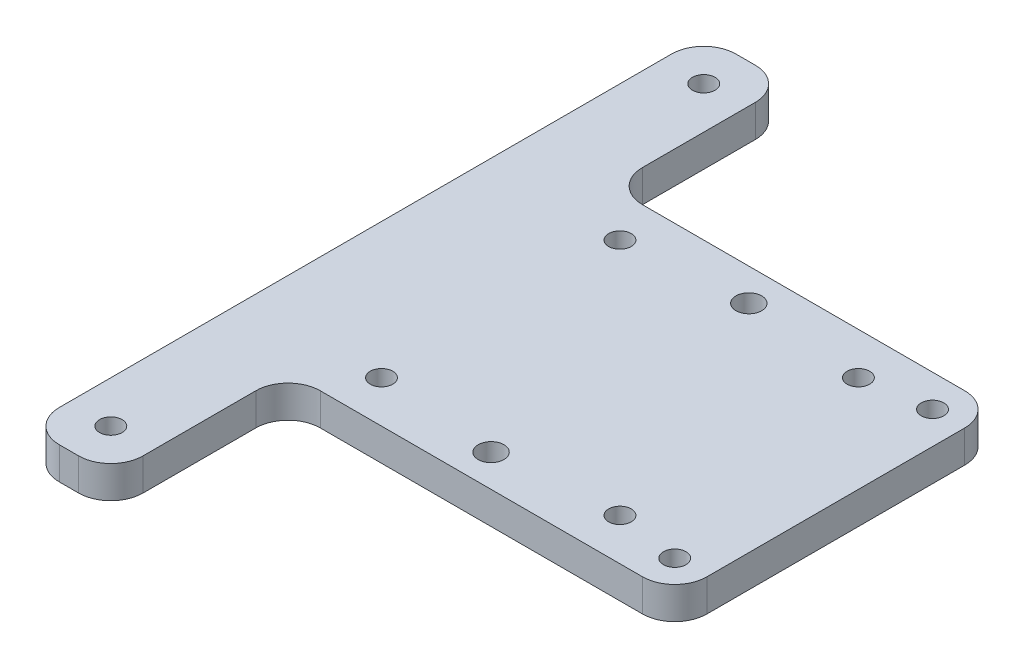
SolidWorks part; units mm, degrees
ref_plane "정면" through (0, 0, 0) normal (0, 0, 1) x (1, 0, 0)
ref_plane "윗면" through (0, 0, 0) normal (0, 1, 0) x (1, 0, 0)
ref_plane "우측면" through (0, 0, 0) normal (1, 0, 0) x (0, 0, -1)
sketch "스케치2" plane through (0, 0, 0) normal (0, 1, 0) x (1, 0, 0)
  line L0 (-60, -25) -> (-60, -52.5)
  line L1 (-60, 25) -> (0, 25)
  line L3 (-60, -25) -> (0, -25)
  line L4 (0, 25) -> (0, -25)
  line L5 (-60, 25) -> (0, -25) construction
  line L6 (-60, -25) -> (0, 25) construction
  line L11 (-73, 52.5) -> (-60, 52.5)
  line L12 (-73, 52.5) -> (-73, -52.5)
  line L13 (-73, -52.5) -> (-60, -52.5)
  line L14 (-60, 52.5) -> (-60, 25)
  line L16 (-73, 0) -> (0, 0) construction
  line L17 (-66.5, 52.5) -> (-66.5, -52.5) construction
  point P0 (-30, 0)
  point P5 (0, 0)
  point P11 (-73, 0)
  dimension "D1" = 50
  dimension "D2" = 60
  dimension "D3" = 105
  dimension "D4" = 13
extrude "보스-돌출1" add sketch "스케치2" along normal blind 5
fillet "필렛1" radius 5 8 edges at (-60, 2.5, -25) (0, 2.5, -25) (0, 2.5, 25) (-60, 2.5, 25) (-60, 2.5, 52.5) (-73, 2.5, 52.5) (-60, 2.5, -52.5) (-73, 2.5, -52.5)
sketch "스케치5" plane through (0, 5, 0) normal (0, 1, 0) x (1, 0, 0)
  circle A0 centre (-5, 20) radius 1.75
  circle A1 centre (-5, -20) radius 1.75
  dimension "D1" = 3.5
  dimension "D2" = 3.5
sketch "스케치7" plane through (0, 0, 0) normal (0, -1, 0) x (1, 0, 0)
  circle A0 centre (-66.5, -46) radius 1.75 construction
  circle A1 centre (-66.5, 46) radius 1.75 construction
  circle A2 centre (-66.5, -46) radius 1.75
  circle A3 centre (-66.5, 46) radius 1.75
extrude "컷-돌출5" cut sketch "스케치7" against normal through all
sketch "스케치8" plane through (0, 5, 0) normal (0, 1, 0) x (1, 0, 0)
  circle A0 centre (-5, 20) radius 1.75
  circle A1 centre (-5, -20) radius 1.75
  dimension "D1" = 3.5
  dimension "D2" = 3.5
extrude "컷-돌출6" cut sketch "스케치8" against normal through all
sketch "스케치9" plane through (0, 5, 0) normal (0, 1, 0) x (1, 0, 0)
  line L0 (-5, 25) -> (-55, 25) construction
  line L1 (-15, 18.5) -> (-52, 18.5) construction
  line L2 (-15, 18.5) -> (-15, -18.5) construction
  line L3 (-15, -18.5) -> (-52, -18.5) construction
  line L4 (-52, 18.5) -> (-52, -18.5) construction
  line L5 (-15, 18.5) -> (-52, -18.5) construction
  line L6 (-15, -18.5) -> (-52, 18.5) construction
  line L7 (-33.5, 25) -> (-33.5, -25) construction
  line L8 (-55, -25) -> (-5, -25) construction
  line L9 (0, -20) -> (0, 20) construction
  line L10 (-52, 0) -> (-15, 0) construction
  circle A0 centre (-52, 18.5) radius 1.75
  circle A1 centre (-52, -18.5) radius 1.75
  circle A2 centre (-15, -18.5) radius 1.75
  circle A3 centre (-15, 18.5) radius 1.75
  circle A4 centre (-33.5, 20) radius 2
  circle A5 centre (-33.5, -20) radius 2
  point P0 (-33.5, 0)
  dimension "D3" = 3.5
  dimension "D4" = 4
  dimension "D1" = 37
  dimension "D2" = 15
  dimension "D5" = 40
extrude "컷-돌출7" cut sketch "스케치9" against normal through all
ref_plane "평면1" through (-33.5, 0, 0) normal (1, 0, 0) x (0, 0, -1)
